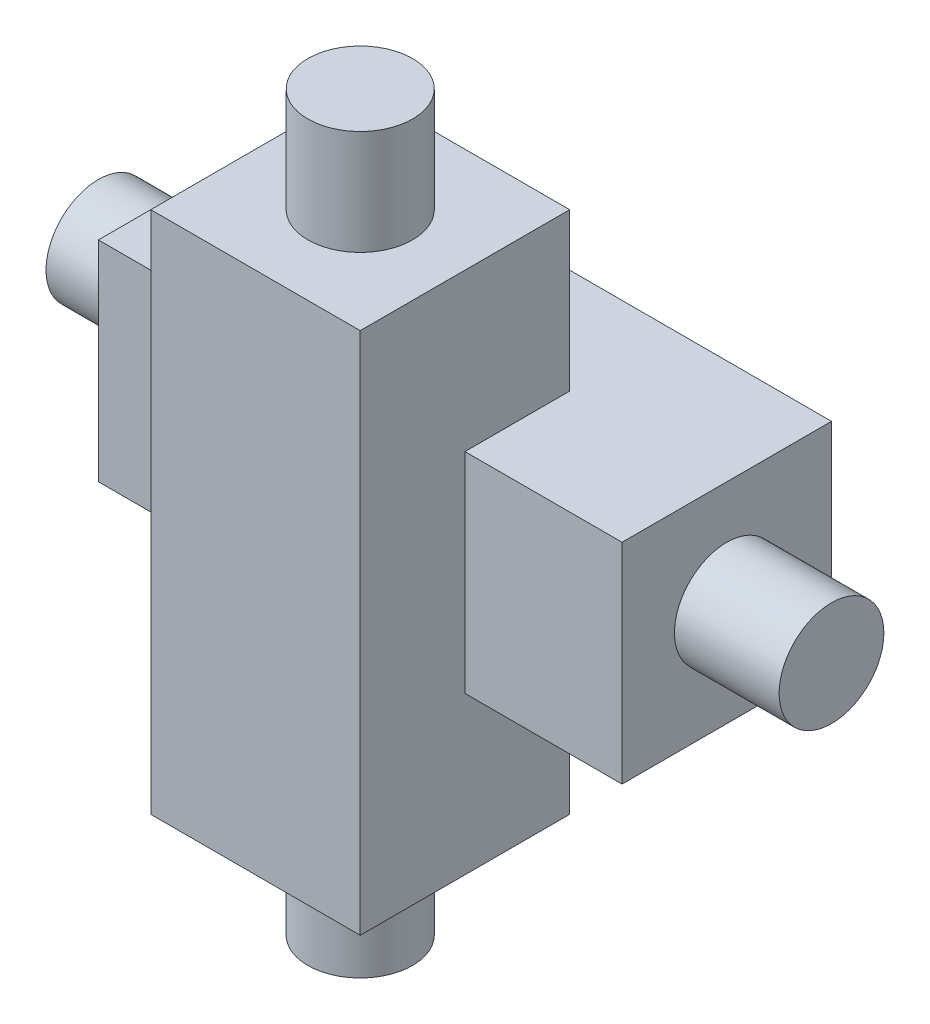
SolidWorks part; units mm, degrees
ref_plane "Front Plane" through (0, 0, 0) normal (0, 0, 1) x (1, 0, 0)
ref_plane "Top Plane" through (0, 0, 0) normal (0, 1, 0) x (1, 0, 0)
ref_plane "Right Plane" through (0, 0, 0) normal (1, 0, 0) x (0, 0, -1)
sketch "Sketch1" plane through (0, 0, 0) normal (0, 1, 0) x (1, 0, 0)
  line L1 (-10, 10) -> (10, 10)
  line L2 (-10, 10) -> (-10, -10)
  line L3 (-10, -10) -> (10, -10)
  line L4 (10, 10) -> (10, -10)
  line L5 (-10, 10) -> (10, -10) construction
  line L6 (-10, -10) -> (10, 10) construction
  point P0 (0, 0)
  dimension "D1" = 20
  dimension "D2" = 20
extrude "Boss-Extrude1" add sketch "Sketch1" along normal mid plane 50
sketch "Sketch2" plane through (0, 0, 0) normal (1, 0, 0) x (0, 0, -1)
  line L5 (10, 25) -> (10, -25) construction
  line L6 (0, 10) -> (20, 10)
  line L7 (0, 10) -> (0, -10)
  line L8 (0, -10) -> (20, -10)
  line L9 (20, 10) -> (20, -10)
  line L10 (0, 10) -> (20, -10) construction
  line L11 (0, -10) -> (20, 10) construction
  point P0 (10, 0)
  dimension "D1" = 20
  dimension "D2" = 20
extrude "Boss-Extrude2" add sketch "Sketch2" along normal mid plane 50
sketch "Sketch3" plane through (0, 0, 0) normal (0, 1, 0) x (1, 0, 0)
  circle A0 centre (0, 0) radius 5
  dimension "D1" = 10
extrude "Boss-Extrude3" add sketch "Sketch3" along normal mid plane 70
sketch "Sketch5" plane through (0, 0, 0) normal (1, 0, 0) x (0, 0, -1)
  line L0 (0, -10) -> (20, 10) construction
  circle A0 centre (10, 0) radius 5
  dimension "D1" = 10
extrude "Boss-Extrude4" add sketch "Sketch5" along normal mid plane 70
